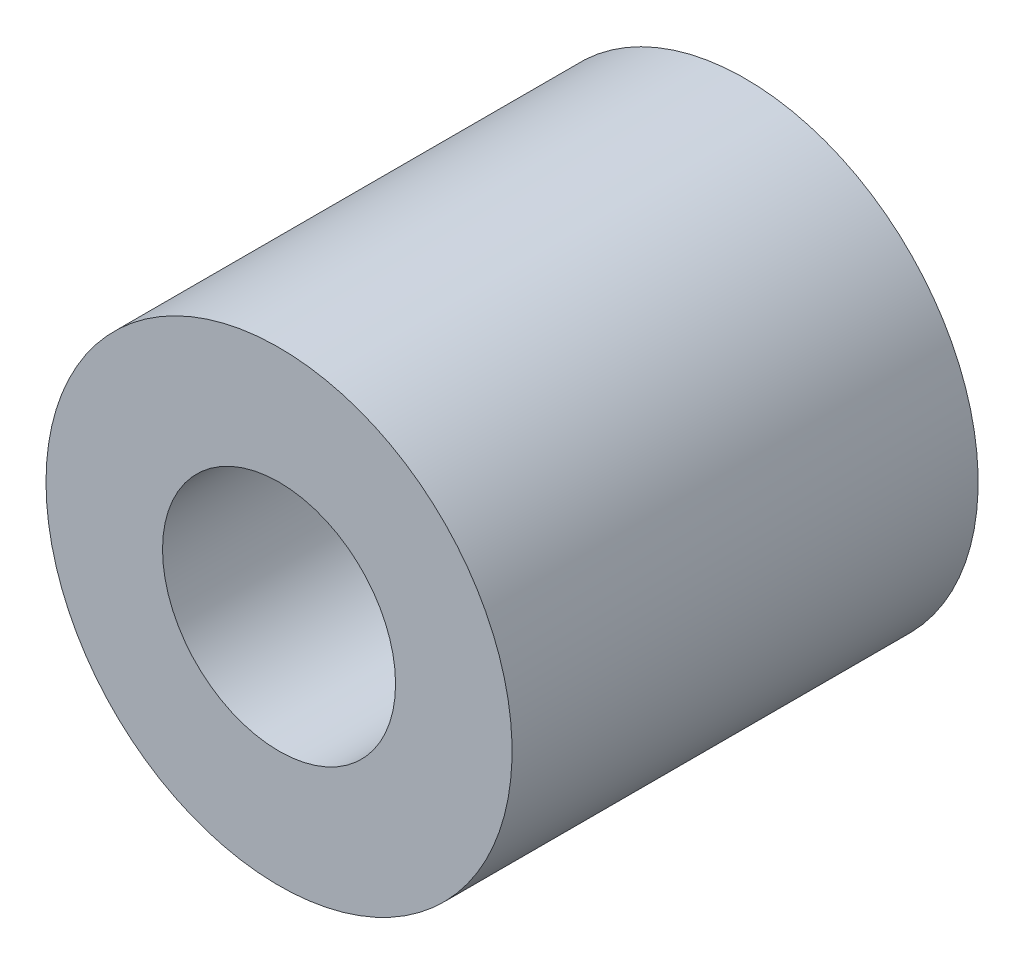
SolidWorks part; units mm, degrees
ref_plane "Front Plane" through (0, 0, 0) normal (0, 0, 1) x (1, 0, 0)
ref_plane "Top Plane" through (0, 0, 0) normal (0, 1, 0) x (1, 0, 0)
ref_plane "Right Plane" through (0, 0, 0) normal (1, 0, 0) x (0, 0, -1)
sketch "AnnulusProfile" plane through (0, 0, 0) normal (0, 1, 0) x (1, 0, 0)
  line L1 (3, 0) -> (6, 0)
  line L2 (3, 0) -> (3, -12)
  line L3 (3, -12) -> (6, -12)
  line L4 (6, 0) -> (6, -12)
  line L5 (0, 0) -> (0, -20) construction
  dimension "inner_radius_mm" = 3
  dimension "outer_radius_mm" = 6
  dimension "height_mm" = 12
revolve "Revolution" add sketch "AnnulusProfile" angle 360 about L5
